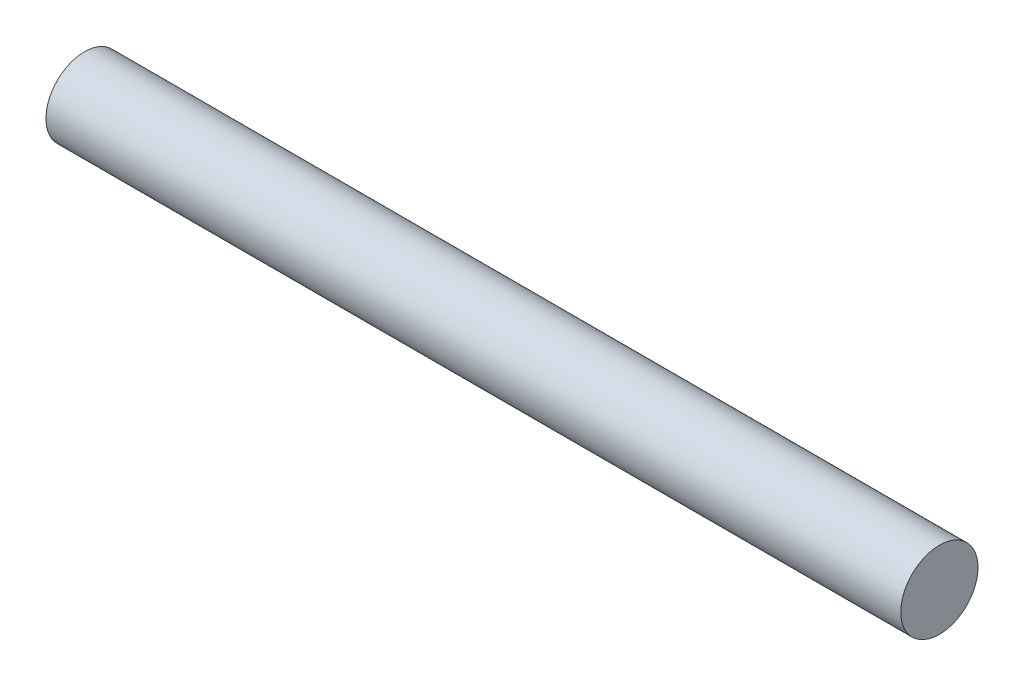
SolidWorks part; units mm, degrees
material "ASTM A36 Steel"
ref_plane "Front Plane" through (0, 0, 0) normal (0, 0, 1) x (1, 0, 0)
ref_plane "Top Plane" through (0, 0, 0) normal (0, 1, 0) x (1, 0, 0)
ref_plane "Right Plane" through (0, 0, 0) normal (1, 0, 0) x (0, 0, -1)
sketch "Sketch1" plane through (0, 0, 0) normal (1, 0, 0) x (0, 0, -1)
  circle A0 centre (0, 0) radius 22.5
  dimension "D1" = 45
extrude "Boss-Extrude1" add sketch "Sketch1" along normal blind 498
